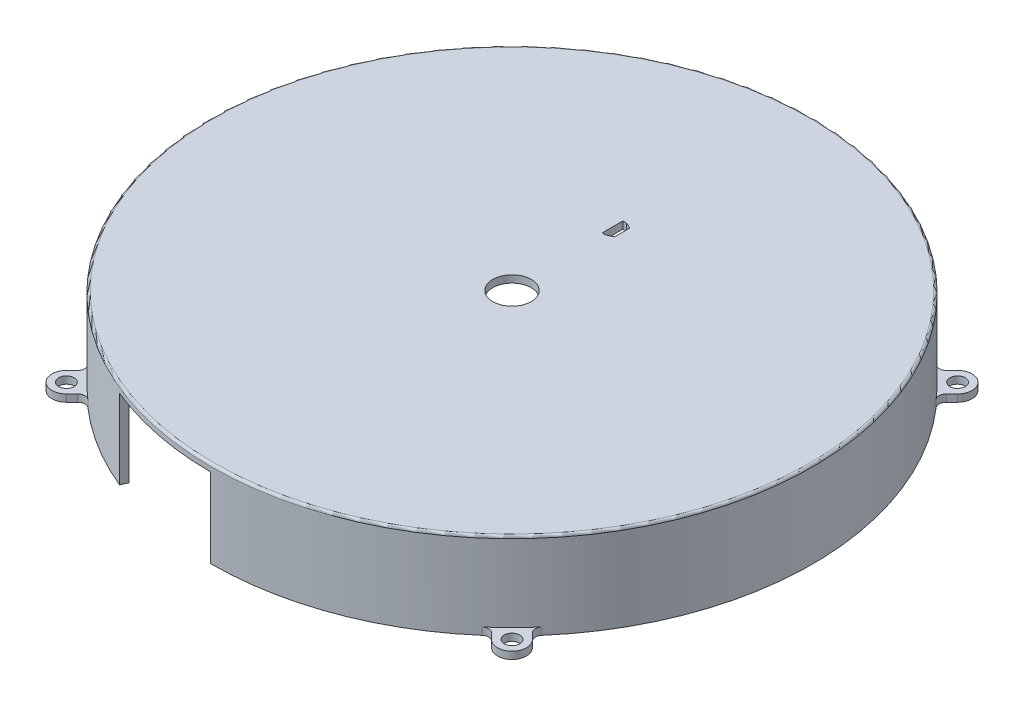
SolidWorks part; units mm, degrees
ref_plane "Спереди" through (0, 0, 0) normal (0, 0, 1) x (1, 0, 0)
ref_plane "Сверху" through (0, 0, 0) normal (0, 1, 0) x (1, 0, 0)
ref_plane "Справа" through (0, 0, 0) normal (1, 0, 0) x (0, 0, -1)
sketch "Эскиз1" plane through (0, 0, 0) normal (0, 1, 0) x (1, 0, 0)
  line L0 (0, 61) -> (0, -61) construction
  line L1 (0, -61) -> (0, -62.5) construction
  line L2 (-61, 0) -> (0, 0) construction
  line L3 (-43.1335, -43.1335) -> (0, 0) construction
  line L4 (-30.5, -30.5) -> (0, 0) construction
  line L5 (0, -61) -> (0, 0) construction
  line L6 (0, 0) -> (-43.1335, -43.1335) construction
  line L7 (0, 0) -> (-21.5668, -52.0668) construction
  line L8 (-21.5668, -52.0668) -> (-23.9177, -57.7425) construction
  line L9 (-23.9177, -57.7425) -> (-23.3437, -56.3567) construction
  line L10 (-21.4282, -52.1242) -> (-23.7791, -57.7999)
  line L11 (-0.15, -61) -> (-0.15, -62.5)
  line L12 (-0.15, -61) -> (0, -61)
  arc A0 (0, -61) -> (-23.205, -56.4139) centre (0, 0) ccw
  arc A1 (-0.15, -62.4998) -> (-23.7791, -57.7997) centre (0, 0) ccw
  dimension "D1" = 122
  dimension "D2" = 125
  dimension "D3" = 0.15
  dimension "D4" = 0.15
extrude "Бобышка-Вытянуть1" add sketch "Эскиз1" along normal blind 16.5 contours L11 A1 L10 A0 L12
sketch "Эскиз2" plane through (0, 16.5, 0) normal (0, 1, 0) x (1, 0, 0)
  line L0 (-0.25, 22.4375) -> (-0.25, 21.3625)
  line L1 (-1, 24.05) -> (-0.25, 24.05)
  line L2 (-1, 24.05) -> (-1, 19.75)
  line L3 (-1, 19.75) -> (-0.25, 19.75)
  line L4 (1, 23.5) -> (1, 20.3)
  line L5 (-1, 24.05) -> (1, 19.75) construction
  line L6 (-1, 19.75) -> (1, 24.05) construction
  line L7 (-1, 23.5) -> (-0.7442, 23.5)
  line L8 (-1, 20.3) -> (-0.7442, 20.3)
  line L9 (-0.25, 19.75) -> (1, 20.3)
  line L10 (1, 23.5) -> (-0.25, 24.05)
  line L11 (0.7442, 23.5) -> (1, 23.5)
  line L12 (-1, 24.05) -> (1, 24.05) construction
  line L14 (-1, 23.5) -> (1, 23.5) construction
  line L15 (-0.25, 24.05) -> (-0.25, 19.75) construction
  line L16 (0.7442, 20.3) -> (1, 20.3)
  line L17 (-1, 19.75) -> (1, 19.75) construction
  line L18 (-1, 20.3) -> (1, 20.3) construction
  circle A0 centre (0, 0) radius 62.5
  circle A1 centre (0, 0) radius 4
  circle A2 centre (0, 0) radius 60 construction
  circle A3 centre (0, 0) radius 21.9 construction
  point P6 (0, 21.9)
  line M4 (-0.15, -61) -> (-0.15, -62.4998)
  arc M5 (-0.15, -62.4998) -> (-23.7791, -57.7997) centre (0, 0) ccw
  line M6 (-23.7791, -57.7997) -> (-23.205, -56.4139)
  arc M7 (-23.205, -56.4139) -> (0, -61) centre (0, 0) cw
  line M8 (0, -61) -> (-0.15, -61)
  dimension "D1" = 8
  dimension "D2" = 120
  dimension "D3" = 43.8
  dimension "D4" = 4.3
  dimension "D5" = 2
  dimension "D6" = 0.75
  dimension "D7" = 0.55
  dimension "D8" = 0.55
extrude "Бобышка-Вытянуть2" add sketch "Эскиз2" along normal blind 1.5 contours M8 M4 M5 M6 M7 | A0 A1 L10 L4 L9 L3 L2 L1 M6 M4 M8 M7
fillet "Скругление1" radius 0.5 1 edges at (0, 18, 62.5)
sketch "Эскиз3" plane through (0, 0, 0) normal (0, -1, 0) x (1, 0, 0)
  line L0 (0, 62.5) -> (0, -62.5) construction
  line L1 (0, -62.5) -> (-62.5, 0) construction
  line L2 (-62.5, 0) -> (62.5, 0) construction
  line L3 (0, 0) -> (-31.25, -31.25) construction
  line L4 (-31.25, -31.25) -> (-44.1942, -44.1942) construction
  line L5 (-44.1942, -44.1942) -> (-46.3155, -46.3155) construction
  line L6 (-44.1942, 48.4368) -> (-42.0219, 46.2646)
  line L7 (-48.4368, 44.1942) -> (-46.0439, 41.8013)
  line L8 (-44.1942, 44.1942) -> (-46.3155, 46.3155) construction
  line L9 (48.4368, 44.1942) -> (46.2646, 42.0219)
  line L10 (-48.4368, -44.1942) -> (-46.2646, -42.0219)
  line L11 (-44.1942, -48.4368) -> (-41.8013, -46.0439)
  line L12 (44.1942, 48.4368) -> (41.8013, 46.0439)
  line L13 (44.1942, 44.1942) -> (46.3155, 46.3155) construction
  line L14 (44.1942, -48.4368) -> (42.0219, -46.2646)
  line L15 (48.4368, -44.1942) -> (46.0439, -41.8013)
  line L16 (44.1942, -44.1942) -> (46.3155, -46.3155) construction
  arc A0 (-23.7791, 57.7997) -> (-0.15, 62.4998) centre (0, 0) ccw construction
  arc A1 (-48.4368, -44.1942) -> (-44.1942, -48.4368) centre (-46.3155, -46.3155) ccw
  circle A2 centre (-46.3155, -46.3155) radius 1.6
  circle A3 centre (0, 0) radius 62.1884
  arc A4 (-44.1942, 48.4368) -> (-48.4368, 44.1942) centre (-46.3155, 46.3155) ccw
  circle A5 centre (-46.3155, 46.3155) radius 1.6
  arc A6 (48.4368, 44.1942) -> (44.1942, 48.4368) centre (46.3155, 46.3155) ccw
  circle A7 centre (46.3155, 46.3155) radius 1.6
  arc A8 (44.1942, -48.4368) -> (48.4368, -44.1942) centre (46.3155, -46.3155) ccw
  circle A9 centre (46.3155, -46.3155) radius 1.6
  point P14 (-44.1942, -44.1942)
  point P22 (-44.1942, 44.1942)
  point P33 (44.1942, 44.1942)
  point P41 (44.1942, -44.1942)
  point P47 (0, 0)
  arc M6 (-23.7791, 57.7997) -> (-0.15, 62.4998) centre (0, 0) ccw
  dimension "D1" = 6
  dimension "D3" = 3.2
  dimension "D2" = 0
  dimension "D4" = 4
extrude "Бобышка-Вытянуть4" add sketch "Эскиз3" against normal blind 1.5 contours L6 A4 L7 A5 M6 | L9 A6 L12 A7 M6 | L10 A1 L11 A2 M6 | L14 A8 L15 A9 M6
fillet "Скругление2" radius 1.5 8 edges at (-46.2646, 0.75, -42.0219) (-42.0219, 0.75, -46.2646) (42.0219, 0.75, -46.2646) (46.2646, 0.75, -42.0219) (46.2646, 0.75, 42.0219) (42.0219, 0.75, 46.2646) (-42.0219, 0.75, 46.2646) (-46.2646, 0.75, 42.0219)
